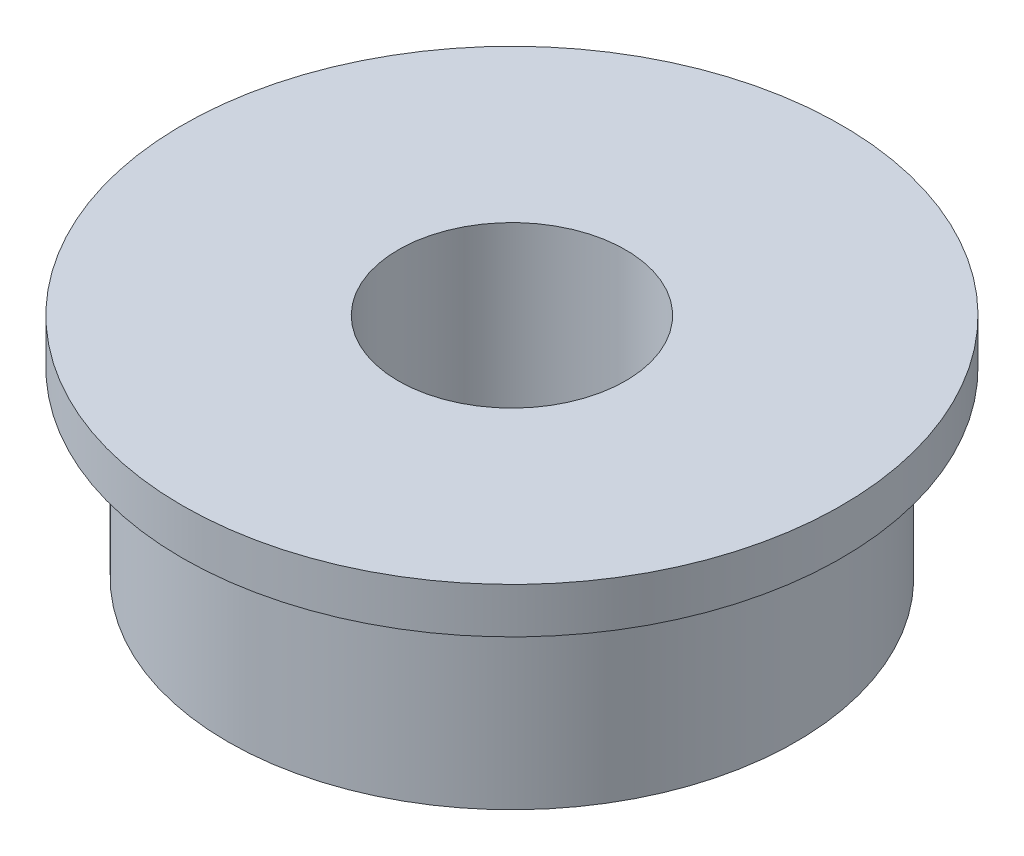
SolidWorks part; units mm, degrees
ref_plane "前视基准面" through (0, 0, 0) normal (0, 0, 1) x (1, 0, 0)
ref_plane "上视基准面" through (0, 0, 0) normal (0, 1, 0) x (1, 0, 0)
ref_plane "右视基准面" through (0, 0, 0) normal (1, 0, 0) x (0, 0, -1)
sketch "草图1" plane through (0, 0, 0) normal (0, 1, 0) x (1, 0, 0)
  circle A0 centre (0, 0) radius 2
  circle A1 centre (0, 0) radius 5
  dimension "D1" = 4
  dimension "D2" = 10
extrude "凸台-拉伸1" add sketch "草图1" along normal blind 4
sketch "草图2" plane through (0, 4, 0) normal (0, 1, 0) x (1, 0, 0)
  circle A0 centre (0, 0) radius 5.8
  circle A1 centre (0, 0) radius 5 construction
  circle A2 centre (0, 0) radius 5
  dimension "D1" = 11.6
extrude "凸台-拉伸2" add sketch "草图2" against normal blind 0.8
